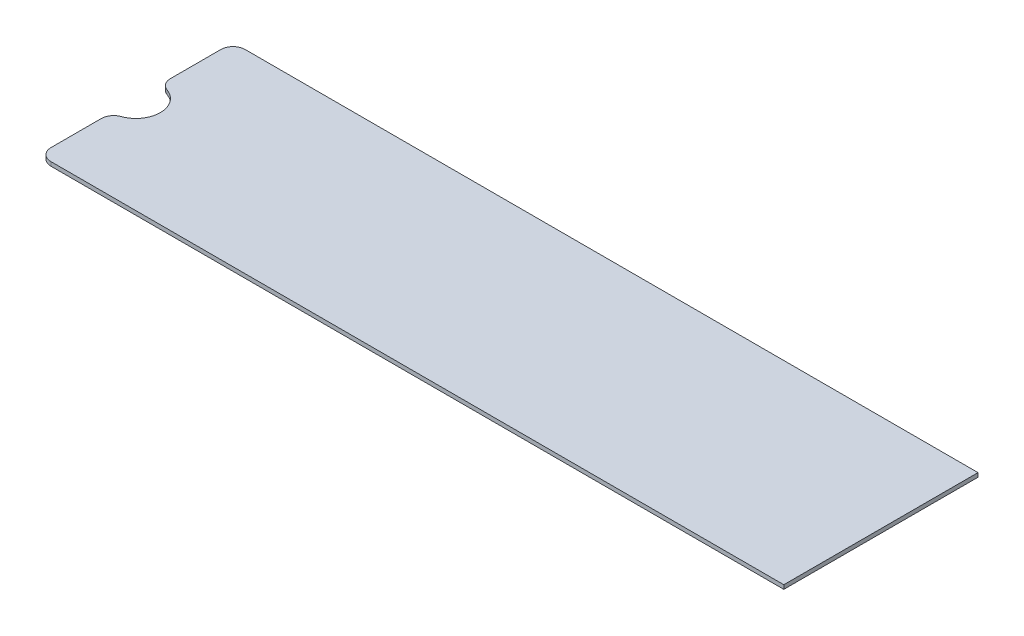
SolidWorks part; units mm, degrees
ref_plane "Front Plane" through (0, 0, 0) normal (0, 0, 1) x (1, 0, 0)
ref_plane "Top Plane" through (0, 0, 0) normal (0, 1, 0) x (1, 0, 0)
ref_plane "Right Plane" through (0, 0, 0) normal (1, 0, 0) x (0, 0, -1)
sketch "Sketch1" plane through (0, 0, 0) normal (0, 1, 0) x (1, 0, 0)
  line L1 (-305, -79.5) -> (305, -79.5)
  line L2 (-305, -79.5) -> (-305, 79.5)
  line L3 (-305, 79.5) -> (305, 79.5)
  line L4 (305, -79.5) -> (305, 79.5)
  line L5 (-305, -79.5) -> (305, 79.5) construction
  line L6 (-305, 79.5) -> (305, -79.5) construction
  arc A0 (-305, 20) -> (-305, -20) centre (-305, 0) cw
  point P0 (0, 0)
  dimension "D3" = 20
  dimension "D1" = 159
  dimension "D2" = 610
extrude "Boss-Extrude1" add sketch "Sketch1" along normal mid plane 3.3 contours L2 A0 L1 L4 L3
fillet "Fillet1" radius 10 4 edges at (-305, 0, -79.5) (-305, 0, 20) (-305, 0, -20) (-305, 0, 79.5)
